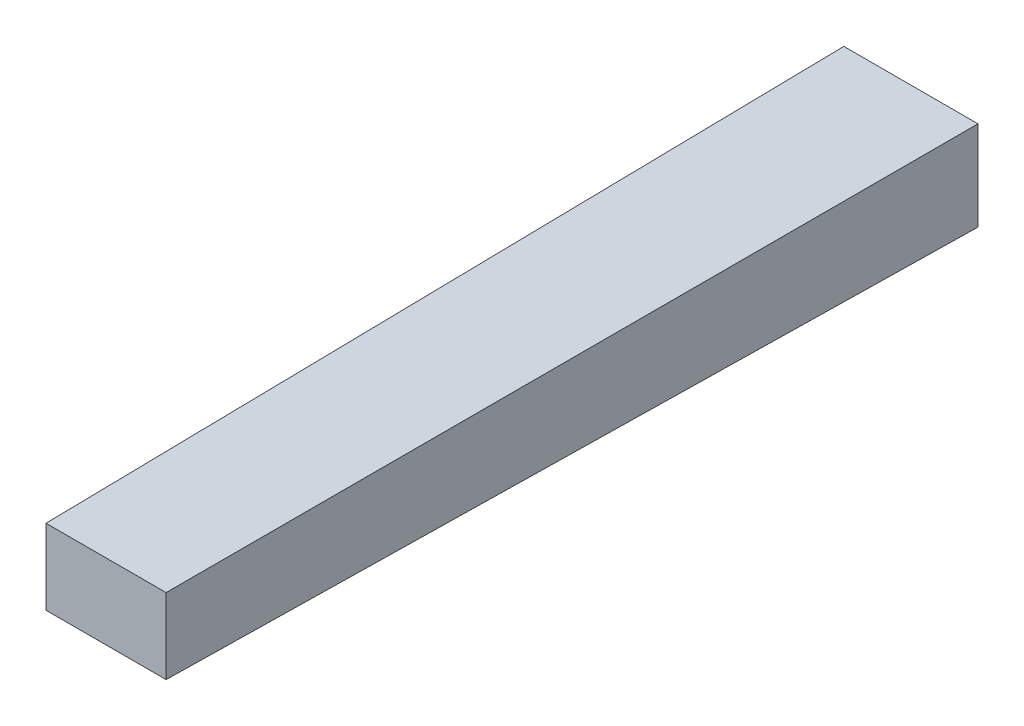
SolidWorks part; units mm, degrees
ref_plane "Front Plane" through (0, 0, 0) normal (0, 0, 1) x (1, 0, 0)
ref_plane "Top Plane" through (0, 0, 0) normal (0, 1, 0) x (1, 0, 0)
ref_plane "Right Plane" through (0, 0, 0) normal (1, 0, 0) x (0, 0, -1)
sketch "Sketch1" plane through (0, 0, 0) normal (0, 0, 1) x (1, 0, 0)
  line L1 (0, 0) -> (9, 0)
  line L2 (0, 0) -> (0, 6)
  line L3 (0, 6) -> (9, 6)
  line L4 (9, 0) -> (9, 6)
  dimension "D1" = 6
  dimension "D2" = 9
extrude "Boss-Extrude1" add sketch "Sketch1" along normal blind 54 draft 0.5
